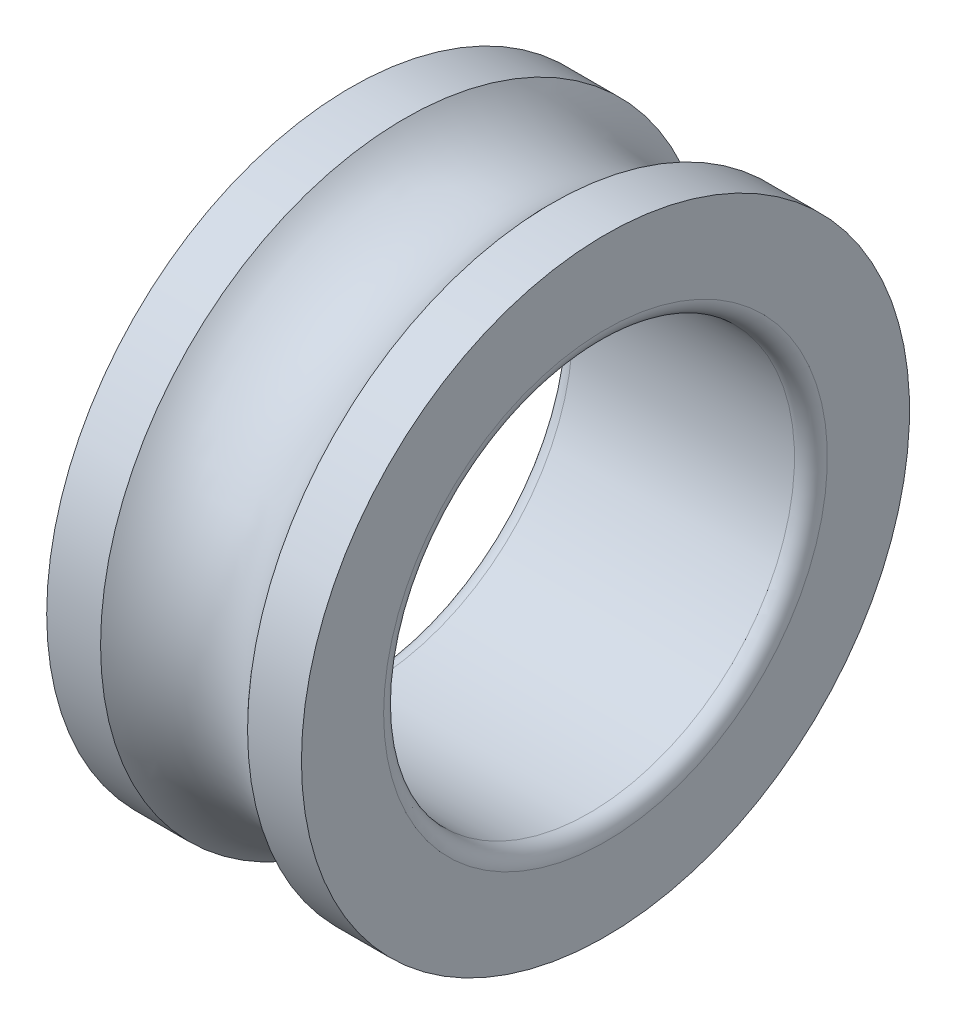
SolidWorks part; units mm, degrees
ref_plane "前视基准面" through (0, 0, 0) normal (0, 0, 1) x (1, 0, 0)
ref_plane "上视基准面" through (0, 0, 0) normal (0, 1, 0) x (1, 0, 0)
ref_plane "右视基准面" through (0, 0, 0) normal (1, 0, 0) x (0, 0, -1)
sketch "草图1" plane through (0, 0, 0) normal (0, 0, 1) x (1, 0, 0)
  line L0 (0, 0) -> (0, 31) construction
  line L1 (0, 31) -> (0, 0) construction
  line L2 (0, 0) -> (29.0599, 0) construction
  line L3 (-15.5, 37) -> (-8.9443, 37)
  line L5 (-15.5, 37) -> (-15.5, 25)
  line L6 (-15.5, 25) -> (15.5, 25)
  line L7 (15.5, 37) -> (15.5, 25)
  line L8 (-15.5, 37) -> (15.5, 25) construction
  line L9 (-15.5, 25) -> (15.5, 37) construction
  line L10 (8.9443, 37) -> (15.5, 37)
  arc A0 (-8.9443, 37) -> (8.9443, 37) centre (0, 45) ccw
  dimension "D1" = 12
  dimension "D2" = 8
  dimension "D3" = 31
  dimension "D4" = 25
  dimension "D5" = 37
revolve "旋转1" add sketch "草图1" angle 360 about L2
fillet "圆角1" radius 2 2 edges at (-15.5, 0, 25) (15.5, 0, 25)
